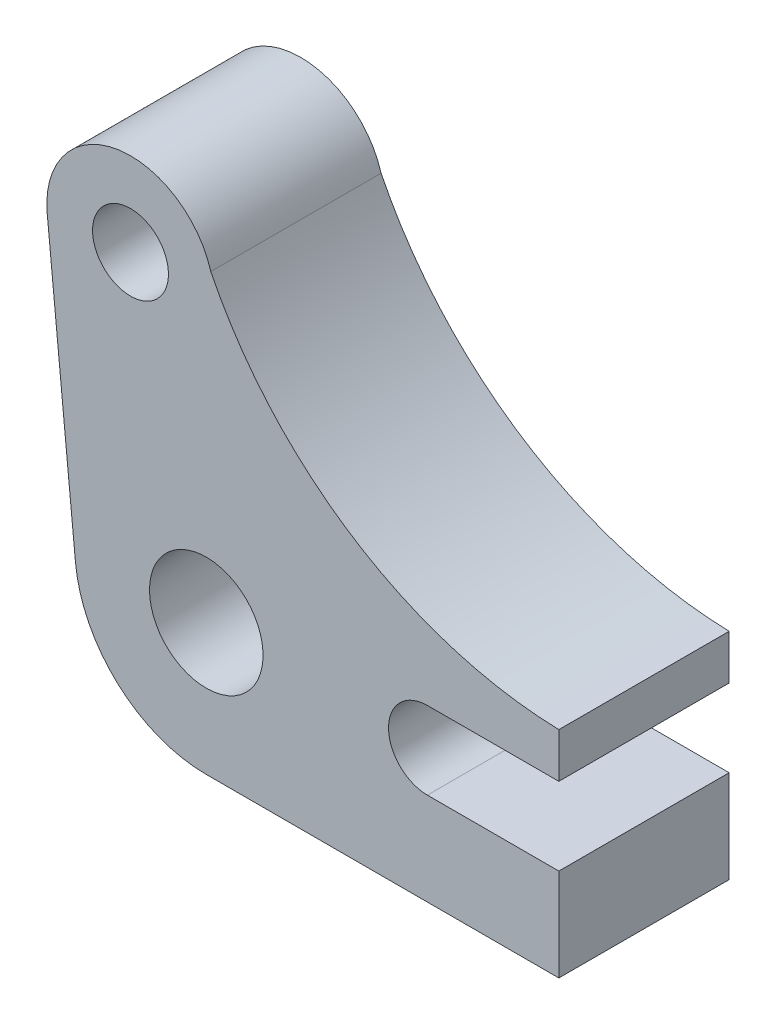
SolidWorks part; units mm, degrees
material "AISI 1020"
ref_plane "Plan de face" through (0, 0, 0) normal (0, 0, 1) x (1, 0, 0)
ref_plane "Plan de dessus" through (0, 0, 0) normal (0, 1, 0) x (1, 0, 0)
ref_plane "Plan de droite" through (0, 0, 0) normal (1, 0, 0) x (0, 0, -1)
sketch "Esquisse1" plane through (0, 0, 0) normal (0, 0, 1) x (1, 0, 0)
  line L0 (-86.6333, -6.9931) -> (-81.9129, -55.1046)
  line L5 (-1.018, -46.4564) -> (-23.018, -46.4564)
  line L7 (-23.018, -59.4564) -> (-1.018, -59.4564)
  line L8 (-1.018, -59.4564) -> (-1.018, -74.9564)
  line L9 (-1.018, -74.9564) -> (-60.018, -74.9564)
  line L13 (-60.018, -52.9564) -> (-60.018, -14.6646) construction
  line L14 (-60.018, -52.9564) -> (-72.7002, -5.6261) construction
  line L15 (-1.018, -46.4564) -> (-1.018, -38.9564)
  arc A0 (-81.9129, -55.1046) -> (-60.018, -74.9564) centre (-60.018, -52.9564) ccw
  arc A3 (-23.018, -59.4564) -> (-23.018, -46.4564) centre (-23.018, -52.9564) cw
  circle A4 centre (-72.7002, -5.6261) radius 6.35
  circle A5 centre (-60.018, -52.9564) radius 9.5
  arc A7 (-1.018, -38.9564) -> (-59.2631, -1.6959) centre (0.7869, 28.0193) cw
  arc A8 (-59.2631, -1.6959) -> (-86.6333, -6.9931) centre (-72.7002, -5.6261) ccw
  point P2 (-47.7667, -14.6646)
  point P3 (0, 0)
  point P12 (-86.6333, -6.9931)
  dimension "D1" = 22
  dimension "D3" = 6.5
  dimension "D4" = 14
  dimension "D10" = 67
  dimension "D15" = 12.7
  dimension "D6" = 59
  dimension "D7" = 22
  dimension "D8" = 49
  dimension "D9" = 0
  dimension "D11" = 0
  dimension "D5" = 0
  dimension "D12" = 15
  dimension "D13" = 22
  dimension "D14" = 0
  dimension "D2" = 36
extrude "Boss.-Extru.1" add sketch "Esquisse1" along normal blind 28.5
equation "\"A\"= 59"
equation "\"B\"= 22"
equation "\"C\"= 28.5"
equation "\"D6@Esquisse1\"=\"A\""
equation "\"D1@Esquisse1\"=\"B\""
equation "\"D13@Esquisse1\"=\"B\""
equation "\"D1@Boss.-Extru.1\"=\"C\""
